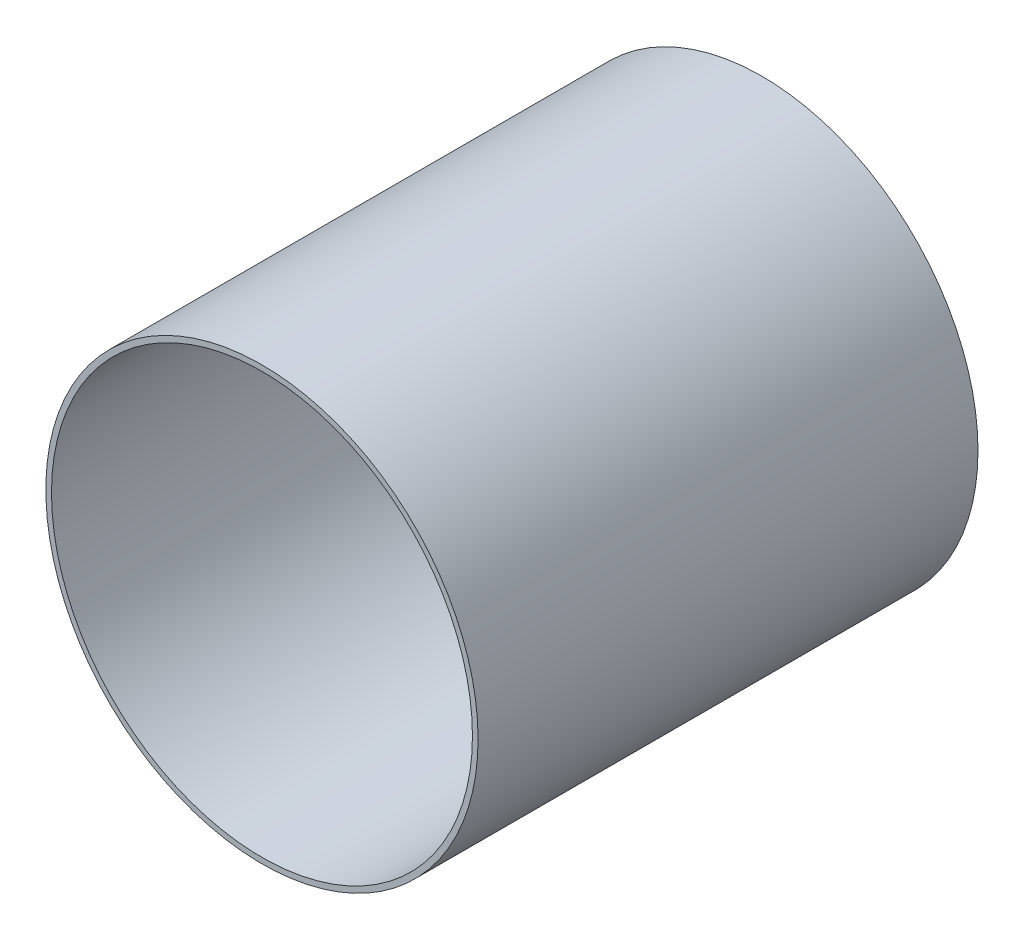
SolidWorks part; units mm, degrees
ref_plane "Ön Düzlem" through (0, 0, 0) normal (0, 0, 1) x (1, 0, 0)
ref_plane "Üst Düzlem" through (0, 0, 0) normal (0, 1, 0) x (1, 0, 0)
ref_plane "Sağ Düzlem" through (0, 0, 0) normal (1, 0, 0) x (0, 0, -1)
sketch "Sketch1" plane through (0, 0, 0) normal (0, 0, 1) x (1, 0, 0)
  circle A0 centre (0, 0) radius 74.65
  circle A1 centre (0, 0) radius 76.65
extrude "Boss-Extrude1" add sketch "Sketch1" along normal blind 177.3
